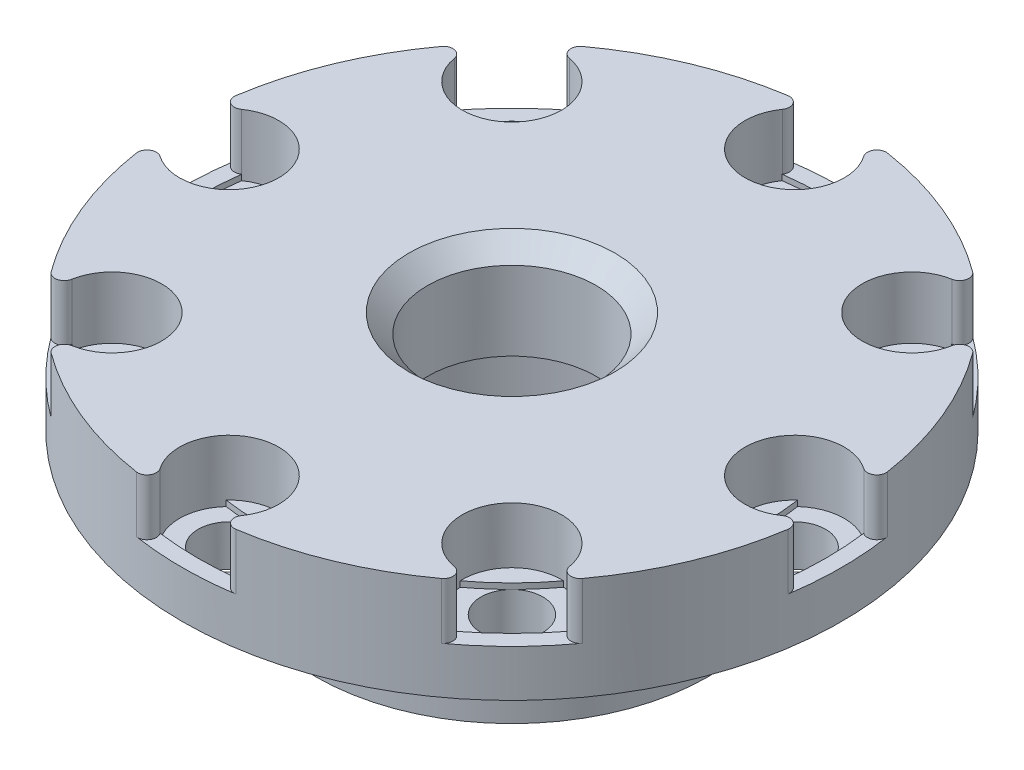
SolidWorks part; units mm, degrees
ref_plane "Front Plane" through (0, 0, 0) normal (0, 0, 1) x (1, 0, 0)
ref_plane "Top Plane" through (0, 0, 0) normal (0, 1, 0) x (1, 0, 0)
ref_plane "Right Plane" through (0, 0, 0) normal (1, 0, 0) x (0, 0, -1)
sketch "Sketch1" plane through (0, 0, 0) normal (0, 1, 0) x (1, 0, 0)
  circle A0 centre (0, 0) radius 12.6 construction
  circle A1 centre (0, 0) radius 12.6
  circle A2 centre (0, 0) radius 8.5 construction
  circle A3 centre (0, 0) radius 8.5
  arc A4 (17.6, 0) -> (-17.6, 0) centre (0, 0) ccw construction
  arc A5 (17.6, 0) -> (-17.6, 0) centre (0, 0) ccw
ref_plane "Plane1" through (0, 6.1, 0) normal (0, 1, 0) x (1, 0, 0)
sketch "Sketch4" plane through (0, 0, 0) normal (0, 1, 0) x (1, 0, 0)
  circle A0 centre (0, 0) radius 8.49
  circle A1 centre (0, 0) radius 10.49
  dimension "D1" = 16.98
  dimension "D2" = 2
sketch "Sketch2" plane through (0, 6.1, 0) normal (0, 1, 0) x (1, 0, 0)
  line L0 (0, 12.6) -> (0, 17.6) construction
  circle A0 centre (0, 0) radius 17.6
  arc A1 (17.6, 0) -> (-17.6, 0) centre (0, 0) ccw construction
  circle A2 centre (0, 0) radius 12.6 construction
  circle A3 centre (0, 0) radius 15.1 construction
  circle A4 centre (0, 15.1) radius 1.65
  circle A5 centre (10.6773, 10.6773) radius 1.65
  circle A6 centre (15.1, 0) radius 1.65
  circle A7 centre (10.6773, -10.6773) radius 1.65
  circle A8 centre (0, -15.1) radius 1.65
  circle A9 centre (-10.6773, -10.6773) radius 1.65
  circle A10 centre (-15.1, 0) radius 1.65
  circle A11 centre (-10.6773, 10.6773) radius 1.65
  circle A12 centre (0, 0) radius 12.6 construction
  circle A13 centre (0, 0) radius 10.49 construction
  circle A14 centre (0, 0) radius 10.49 construction
  point P10 (0, 15.1)
  dimension "D1" = 3.3
  dimension "D2" = 8
extrude "Boss-Extrude1" add sketch "Sketch2" along normal blind 2.5
sketch "Sketch3" plane through (0, 8.6, 0) normal (0, 1, 0) x (1, 0, 0)
  arc A0 (-13.0977, 11.7563) -> (-9.4589, 8.324) centre (-10.6773, 10.6773) ccw
  arc A1 (-0.9485, 17.5744) -> (-0.8025, 12.5744) centre (0, 15.1) ccw
  arc A2 (11.7563, 13.0977) -> (8.324, 9.4589) centre (10.6773, 10.6773) ccw
  arc A3 (17.5744, 0.9485) -> (12.5744, 0.8025) centre (15.1, 0) ccw
  arc A4 (13.0977, -11.7563) -> (9.4589, -8.324) centre (10.6773, -10.6773) ccw
  arc A5 (-17.5744, -0.9485) -> (-12.5744, 0.8025) centre (-15.1, 0) ccw
  arc A6 (-11.7563, -13.0977) -> (-9.4589, -8.324) centre (-10.6773, -10.6773) ccw
  arc A7 (0.9485, -17.5744) -> (-0.8025, -12.5744) centre (0, -15.1) ccw
  circle A8 centre (0, 0) radius 17.6 construction
  arc A9 (-0.9485, 17.5744) -> (-11.7563, 13.0977) centre (0, 0) ccw
  arc A10 (11.7563, 13.0977) -> (0.9485, 17.5744) centre (0, 0) ccw
  arc A11 (-13.0977, 11.7563) -> (-17.5744, 0.9485) centre (0, 0) ccw
  arc A12 (-17.5744, -0.9485) -> (-13.0977, -11.7563) centre (0, 0) ccw
  arc A13 (17.5744, 0.9485) -> (13.0977, 11.7563) centre (0, 0) ccw
  arc A14 (-11.7563, -13.0977) -> (-0.9485, -17.5744) centre (0, 0) ccw
  arc A15 (0.9485, -17.5744) -> (11.7563, -13.0977) centre (0, 0) ccw
  arc A16 (13.0977, -11.7563) -> (17.5744, -0.9485) centre (0, 0) ccw
  arc A19 (-9.4589, 8.324) -> (-11.7563, 13.0977) centre (-10.6773, 10.6773) ccw
  arc A20 (-12.5744, 0.8025) -> (-17.5744, 0.9485) centre (-15.1, 0) ccw
  arc A22 (-9.4589, -8.324) -> (-13.0977, -11.7563) centre (-10.6773, -10.6773) ccw
  arc A24 (-0.8025, -12.5744) -> (-0.9485, -17.5744) centre (0, -15.1) ccw
  arc A26 (9.4589, -8.324) -> (11.7563, -13.0977) centre (10.6773, -10.6773) ccw
  arc A28 (12.5744, 0.8025) -> (17.5744, -0.9485) centre (15.1, 0) ccw
  arc A30 (8.324, 9.4589) -> (13.0977, 11.7563) centre (10.6773, 10.6773) ccw
  arc A32 (-0.8025, 12.5744) -> (0.9485, 17.5744) centre (0, 15.1) ccw
  dimension "D1" = 5.3
extrude "Boss-Extrude2" add sketch "Sketch3" along normal blind 3
fillet "Fillet1" radius 0.5 16 edges at (-0.9485, 10.1, -17.5744) (0.9485, 10.1, -17.5744) (0.9485, 10.1, 17.5744) (-0.9485, 10.1, 17.5744) (13.0977, 10.1, 11.7563) (11.7563, 10.1, 13.0977) (17.5744, 10.1, -0.9485) (17.5744, 10.1, 0.9485) (11.7563, 10.1, -13.0977) (13.0977, 10.1, -11.7563) (-13.0977, 10.1, -11.7563) (-11.7563, 10.1, -13.0977) (-17.5744, 10.1, 0.9485) (-17.5744, 10.1, -0.9485) (-11.7563, 10.1, 13.0977) (-13.0977, 10.1, 11.7563)
sketch "Sketch8" plane through (0, 11.6, 0) normal (0, 1, 0) x (1, 0, 0)
  circle A5 centre (0, 0) radius 10.49 construction
  circle A6 centre (0, 0) radius 10.49
extrude "Boss-Extrude4" add sketch "Sketch8" against normal up to surface (5.5 mm away) up to face at (0, 6.1, 17.6)
sketch "Sketch9" plane through (0, 11.6, 0) normal (0, 1, 0) x (1, 0, 0)
  circle A1 centre (0, 0) radius 10.49
  circle A2 centre (0, 0) radius 10.49
  dimension "D1" = 0
extrude "Boss-Extrude5" add sketch "Sketch9" against normal up to surface (11.6 mm away) up to plane "Top Plane"
sketch "Sketch10" plane through (0, 0, 0) normal (0, -1, 0) x (1, 0, 0)
  circle A0 centre (0, 0) radius 8.49 construction
  circle A1 centre (0, 0) radius 8.49
extrude "Cut-Extrude2" cut sketch "Sketch10" against normal offset from surface (6.4 mm away) 0.3 up to plane "Plane1" offset beyond the face yes
chamfer "Chamfer3" distance 0.5 angle 45 1 edges at (0, 0, -8.49)
sketch "Sketch11" plane through (0, 6.4, 0) normal (0, -1, 0) x (1, 0, 0)
  circle A0 centre (0, 0) radius 4.5
  dimension "D1" = 9
extrude "Cut-Extrude3" cut sketch "Sketch11" against normal through all
chamfer "Chamfer4" distance 1 angle 45 1 edges at (0, 11.6, -4.5)
sketch "Sketch12" plane through (0, 8.6, 0) normal (0, 1, 0) x (1, 0, 0)
  arc A0 (16.6076, -2.1794) -> (16.6076, 2.1794) centre (0, 0) ccw
  arc A1 (13.3076, -1.9519) -> (13.3076, 1.9519) centre (0, 0) ccw
  arc A2 (16.6076, 2.1794) -> (13.3076, 1.9519) centre (15.1, 0) ccw
  arc A3 (13.3076, -1.9519) -> (16.6076, -2.1794) centre (15.1, 0) ccw
  arc A4 (8.0297, -10.7901) -> (10.7901, -8.0297) centre (0, 0) ccw
  arc A5 (13.2844, -10.2023) -> (10.7901, -8.0297) centre (10.6773, -10.6773) ccw
  arc A6 (10.2023, -13.2844) -> (13.2844, -10.2023) centre (0, 0) ccw
  arc A7 (8.0297, -10.7901) -> (10.2023, -13.2844) centre (10.6773, -10.6773) ccw
  arc A8 (-1.9519, -13.3076) -> (1.9519, -13.3076) centre (0, 0) ccw
  arc A9 (2.1794, -16.6076) -> (1.9519, -13.3076) centre (0, -15.1) ccw
  arc A10 (-2.1794, -16.6076) -> (2.1794, -16.6076) centre (0, 0) ccw
  arc A11 (-1.9519, -13.3076) -> (-2.1794, -16.6076) centre (0, -15.1) ccw
  arc A12 (-10.7901, -8.0297) -> (-8.0297, -10.7901) centre (0, 0) ccw
  arc A13 (-10.2023, -13.2844) -> (-8.0297, -10.7901) centre (-10.6773, -10.6773) ccw
  arc A14 (-13.2844, -10.2023) -> (-10.2023, -13.2844) centre (0, 0) ccw
  arc A15 (-10.7901, -8.0297) -> (-13.2844, -10.2023) centre (-10.6773, -10.6773) ccw
  arc A16 (-13.3076, 1.9519) -> (-13.3076, -1.9519) centre (0, 0) ccw
  arc A17 (-16.6076, -2.1794) -> (-13.3076, -1.9519) centre (-15.1, 0) ccw
  arc A18 (-16.6076, 2.1794) -> (-16.6076, -2.1794) centre (0, 0) ccw
  arc A19 (-13.3076, 1.9519) -> (-16.6076, 2.1794) centre (-15.1, 0) ccw
  arc A20 (-8.0297, 10.7901) -> (-10.7901, 8.0297) centre (0, 0) ccw
  arc A21 (-13.2844, 10.2023) -> (-10.7901, 8.0297) centre (-10.6773, 10.6773) ccw
  arc A22 (-10.2023, 13.2844) -> (-13.2844, 10.2023) centre (0, 0) ccw
  arc A23 (-8.0297, 10.7901) -> (-10.2023, 13.2844) centre (-10.6773, 10.6773) ccw
  arc A24 (1.9519, 13.3076) -> (-1.9519, 13.3076) centre (0, 0) ccw
  arc A25 (-2.1794, 16.6076) -> (-1.9519, 13.3076) centre (0, 15.1) ccw
  arc A26 (2.1794, 16.6076) -> (-2.1794, 16.6076) centre (0, 0) ccw
  arc A27 (1.9519, 13.3076) -> (2.1794, 16.6076) centre (0, 15.1) ccw
  arc A28 (10.7901, 8.0297) -> (8.0297, 10.7901) centre (0, 0) ccw
  arc A29 (10.2023, 13.2844) -> (8.0297, 10.7901) centre (10.6773, 10.6773) ccw
  arc A30 (13.2844, 10.2023) -> (10.2023, 13.2844) centre (0, 0) ccw
  arc A31 (10.7901, 8.0297) -> (13.2844, 10.2023) centre (10.6773, 10.6773) ccw
extrude "Cut-Extrude4" cut sketch "Sketch12" against normal blind 0.3
